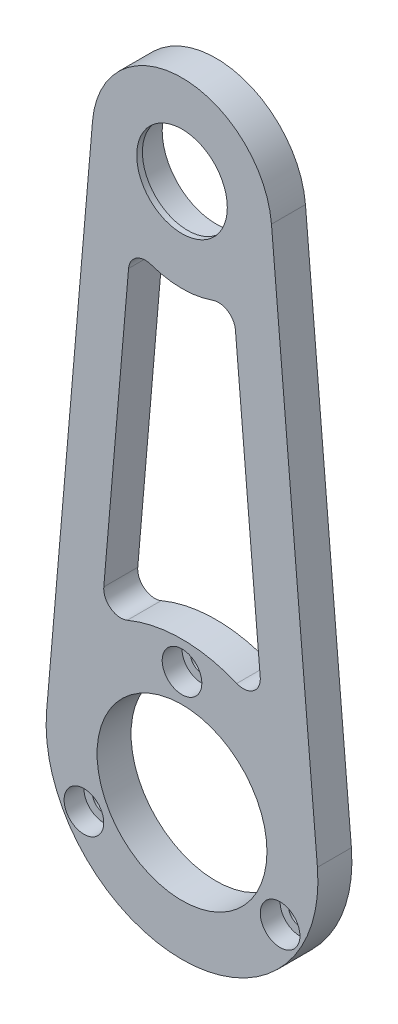
SolidWorks part; units mm, degrees
material "6061 合金"
ref_plane "前视基准面" through (0, 0, 0) normal (0, 0, 1) x (1, 0, 0)
ref_plane "上视基准面" through (0, 0, 0) normal (0, 1, 0) x (1, 0, 0)
ref_plane "右视基准面" through (0, 0, 0) normal (1, 0, 0) x (0, 0, -1)
sketch "草图1" plane through (0, 0, 0) normal (0, 0, 1) x (1, 0, 0)
  line L0 (0, 0) -> (0, 109.1958) construction
  line L1 (-23.9117, 2.0571) -> (-15.7988, 96.3592)
  line L2 (23.9117, 2.0571) -> (15.7988, 96.3592)
  line L3 (-14.2946, 20.5101) -> (-9.0614, 81.3389)
  line L4 (14.2946, 20.5101) -> (9.0614, 81.3389)
  circle A0 centre (0, 0) radius 15
  arc A1 (-23.9117, 2.0571) -> (23.9117, 2.0571) centre (0, 0) ccw
  circle A2 centre (0, 20) radius 2
  arc A4 (15.7988, 96.3592) -> (-15.7988, 96.3592) centre (0, 95) ccw
  circle A5 centre (17.3205, -10) radius 2
  circle A6 centre (-17.3205, -10) radius 2
  arc A7 (-9.0614, 81.3389) -> (9.0614, 81.3389) centre (0, 95) ccw
  arc A8 (14.2946, 20.5101) -> (-14.2946, 20.5101) centre (0, 0) ccw
  point P17 (0, 0)
  dimension "D1" = 4
  dimension "D2" = 20
  dimension "D3" = 30
  dimension "D4" = 48
  dimension "D5" = 4.917
  dimension "D6" = 16.3931
  dimension "D7" = 95
  dimension "D9" = 10
  dimension "D11" = 8
  dimension "D8" = 3
extrude "凸台-拉伸1" add sketch "草图1" along normal blind 6
fillet "圆角1" radius 3 4 edges at (14.2946, 20.5101, 3) (-14.2946, 20.5101, 3) (9.0614, 81.3389, 3) (-9.0614, 81.3389, 3)
sketch "草图3" plane through (0, 0, 0) normal (0, 0, -1) x (-1, 0, 0)
  circle A0 centre (0, 95) radius 9.5
  dimension "D1" = 19
extrude "切除-拉伸2" cut sketch "草图3" against normal blind 6
sketch "草图4" plane through (0, 0, 6) normal (0, 0, 1) x (1, 0, 0)
  circle A0 centre (0, 0) radius 20 construction
  circle A1 centre (0, 20) radius 3.5
  circle A2 centre (17.3205, -10) radius 3.5
  circle A3 centre (-17.3205, -10) radius 3.5
  dimension "D1" = 7
  dimension "D2" = 3
extrude "切除-拉伸3" cut sketch "草图4" against normal blind 3.5
sketch "草图6" plane through (0, 0, 6) normal (0, 0, 1) x (1, 0, 0)
  circle A0 centre (0, 95) radius 9.5
  circle A1 centre (0, 95) radius 8
  dimension "D1" = 19
  dimension "D2" = 16
extrude "凸台-拉伸3" add sketch "草图6" against normal blind 1
